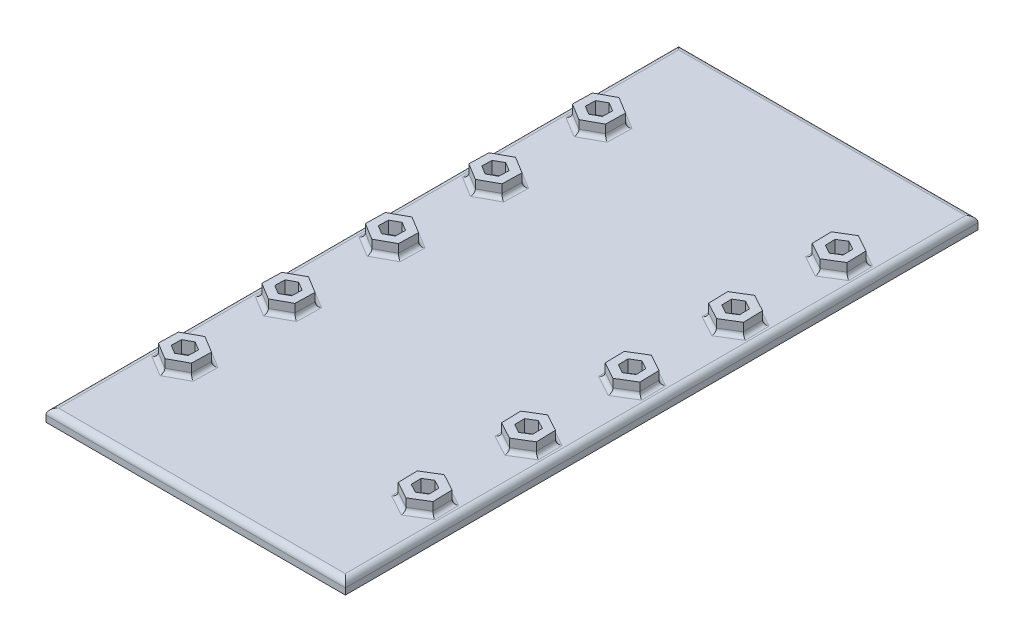
SolidWorks part; units mm, degrees
ref_plane "Front Plane" through (0, 0, 0) normal (0, 0, 1) x (1, 0, 0)
ref_plane "Top Plane" through (0, 0, 0) normal (0, 1, 0) x (1, 0, 0)
ref_plane "Right Plane" through (0, 0, 0) normal (1, 0, 0) x (0, 0, -1)
sketch "Sketch1" plane through (0, 0, 0) normal (0, 1, 0) x (1, 0, 0)
  line L0 (-26.85, 76.4) -> (-31.15, 76.4) construction
  line L1 (-36.15, 76.4) -> (36.15, 76.4)
  line L2 (-36.15, 76.4) -> (-36.15, -76.4)
  line L3 (-36.15, -76.4) -> (36.15, -76.4)
  line L4 (36.15, 76.4) -> (36.15, -76.4)
  line L5 (-36.15, 76.4) -> (36.15, -76.4) construction
  line L6 (-36.15, -76.4) -> (36.15, 76.4) construction
  line L8 (-31.15, 76.4) -> (-31.15, -76.4) construction
  point P0 (0, 0)
  dimension "D1" = 5
extrude "Boss-Extrude1" add sketch "Sketch1" along normal blind 3
sketch "Sketch2" plane through (0, 3, 0) normal (0, 1, 0) x (1, 0, 0)
  line L0 (-29, 76.4) -> (-29, -76.4) construction
  line L1 (-36.15, -76.4) -> (36.15, -76.4) construction
  line L2 (-29, 0) -> (-29, -25) construction
  circle A0 centre (-29, 0) radius 1.2
  circle A1 centre (-29, 0) radius 1.2 construction
  circle A2 centre (-29, -25) radius 1.2
  circle A3 centre (-29, -50) radius 1.2
  circle A4 centre (-29, 0) radius 1.2
  circle A5 centre (-29, -25) radius 1.2
  circle A6 centre (-29, 25) radius 1.2
  circle A7 centre (-29, 0) radius 1.2
  circle A8 centre (-29, 25) radius 1.2
  circle A9 centre (-29, 50) radius 1.2
  point P9 (-29, 0)
  dimension "D3" = 25
  dimension "D1" = 3
  dimension "D2" = 3
extrude "Cut-Extrude1" cut sketch "Sketch2" against normal up to next contours A3 | A2 | A0 | A6 | A9
mirror "Mirror1" about plane through (0, 0, 0) normal (1, 0, 0) of "Cut-Extrude1"
sketch "Sketch5" plane through (0, 3, 0) normal (0, 1, 0) x (1, 0, 0)
  line L0 (-29.1147, 20.2671) -> (-24.9586, 22.5342)
  line L1 (-27.0286, -1.2028) -> (-26.9726, 1.1059)
  line L2 (-26.9726, 1.1059) -> (-28.944, 2.3087)
  line L3 (-28.944, 2.3087) -> (-30.9714, 1.2028)
  line L4 (-30.9714, 1.2028) -> (-31.0274, -1.1059)
  line L5 (-31.0274, -1.1059) -> (-29.056, -2.3087)
  line L6 (-29.056, -2.3087) -> (-27.0286, -1.2028)
  line L7 (-29.0588, -2.4242) -> (-26.93, -1.263)
  line L8 (-26.93, -1.263) -> (-26.8712, 1.1612)
  line L9 (-26.8712, 1.1612) -> (-28.9412, 2.4242)
  line L10 (-28.9412, 2.4242) -> (-31.07, 1.263)
  line L11 (-31.07, 1.263) -> (-31.1288, -1.1612)
  line L12 (-31.1288, -1.1612) -> (-29.0588, -2.4242)
  line L13 (-29.1147, -4.7329) -> (-24.9586, -2.4658)
  line L14 (-24.9586, -2.4658) -> (-24.8438, 2.2671)
  line L15 (-24.8438, 2.2671) -> (-28.8853, 4.7329)
  line L16 (-28.8853, 4.7329) -> (-33.0414, 2.4658)
  line L17 (-33.0414, 2.4658) -> (-33.1562, -2.2671)
  line L18 (-33.1562, -2.2671) -> (-29.1147, -4.7329)
  line L19 (-29, 76.4) -> (-29, -76.4) construction
  line L20 (-36.15, -76.4) -> (36.15, -76.4) construction
  line L21 (-24.9586, 22.5342) -> (-24.8438, 27.2671)
  line L22 (-24.8438, 27.2671) -> (-28.8853, 29.7329)
  line L23 (-28.8853, 29.7329) -> (-33.0414, 27.4658)
  line L24 (-33.0414, 27.4658) -> (-33.1562, 22.7329)
  line L25 (-33.1562, 22.7329) -> (-29.1147, 20.2671)
  line L26 (-26.93, 23.737) -> (-26.8712, 26.1612)
  line L27 (-26.8712, 26.1612) -> (-28.9412, 27.4242)
  line L28 (-28.9412, 27.4242) -> (-31.07, 26.263)
  line L29 (-31.07, 26.263) -> (-31.1288, 23.8388)
  line L30 (-31.1288, 23.8388) -> (-29.0588, 22.5758)
  line L31 (-29.0588, 22.5758) -> (-26.93, 23.737)
  line L32 (-29.1147, 45.2671) -> (-24.9586, 47.5342)
  line L33 (-24.9586, 47.5342) -> (-24.8438, 52.2671)
  line L34 (-24.8438, 52.2671) -> (-28.8853, 54.7329)
  line L35 (-28.8853, 54.7329) -> (-33.0414, 52.4658)
  line L36 (-33.0414, 52.4658) -> (-33.1562, 47.7329)
  line L37 (-33.1562, 47.7329) -> (-29.1147, 45.2671)
  line L38 (-26.93, 48.737) -> (-26.8712, 51.1612)
  line L39 (-26.8712, 51.1612) -> (-28.9412, 52.4242)
  line L40 (-28.9412, 52.4242) -> (-31.07, 51.263)
  line L41 (-31.07, 51.263) -> (-31.1288, 48.8388)
  line L42 (-31.1288, 48.8388) -> (-29.0588, 47.5758)
  line L43 (-29.0588, 47.5758) -> (-26.93, 48.737)
  line L44 (-29.1147, -4.7329) -> (-24.9586, -2.4658)
  line L45 (-24.9586, -2.4658) -> (-24.8438, 2.2671)
  line L46 (-24.8438, 2.2671) -> (-28.8853, 4.7329)
  line L47 (-28.8853, 4.7329) -> (-33.0414, 2.4658)
  line L48 (-33.0414, 2.4658) -> (-33.1562, -2.2671)
  line L49 (-33.1562, -2.2671) -> (-29.1147, -4.7329)
  line L50 (-26.93, -1.263) -> (-26.8712, 1.1612)
  line L51 (-26.8712, 1.1612) -> (-28.9412, 2.4242)
  line L52 (-28.9412, 2.4242) -> (-31.07, 1.263)
  line L53 (-31.07, 1.263) -> (-31.1288, -1.1612)
  line L54 (-31.1288, -1.1612) -> (-29.0588, -2.4242)
  line L55 (-29.0588, -2.4242) -> (-26.93, -1.263)
  line L56 (-29.1147, 20.2671) -> (-24.9586, 22.5342)
  line L57 (-24.9586, 22.5342) -> (-24.8438, 27.2671)
  line L58 (-24.8438, 27.2671) -> (-28.8853, 29.7329)
  line L59 (-28.8853, 29.7329) -> (-33.0414, 27.4658)
  line L60 (-33.0414, 27.4658) -> (-33.1562, 22.7329)
  line L61 (-33.1562, 22.7329) -> (-29.1147, 20.2671)
  line L62 (-26.93, 23.737) -> (-26.8712, 26.1612)
  line L63 (-26.8712, 26.1612) -> (-28.9412, 27.4242)
  line L64 (-28.9412, 27.4242) -> (-31.07, 26.263)
  line L65 (-31.07, 26.263) -> (-31.1288, 23.8388)
  line L66 (-31.1288, 23.8388) -> (-29.0588, 22.5758)
  line L67 (-29.0588, 22.5758) -> (-26.93, 23.737)
  line L68 (-29.1147, -29.7329) -> (-24.9586, -27.4658)
  line L69 (-24.9586, -27.4658) -> (-24.8438, -22.7329)
  line L70 (-24.8438, -22.7329) -> (-28.8853, -20.2671)
  line L71 (-28.8853, -20.2671) -> (-33.0414, -22.5342)
  line L72 (-33.0414, -22.5342) -> (-33.1562, -27.2671)
  line L73 (-33.1562, -27.2671) -> (-29.1147, -29.7329)
  line L74 (-26.93, -26.263) -> (-26.8712, -23.8388)
  line L75 (-26.8712, -23.8388) -> (-28.9412, -22.5758)
  line L76 (-28.9412, -22.5758) -> (-31.07, -23.737)
  line L77 (-31.07, -23.737) -> (-31.1288, -26.1612)
  line L78 (-31.1288, -26.1612) -> (-29.0588, -27.4242)
  line L79 (-29.0588, -27.4242) -> (-26.93, -26.263)
  line L80 (-29.1147, -4.7329) -> (-24.9586, -2.4658)
  line L81 (-24.9586, -2.4658) -> (-24.8438, 2.2671)
  line L82 (-24.8438, 2.2671) -> (-28.8853, 4.7329)
  line L83 (-28.8853, 4.7329) -> (-33.0414, 2.4658)
  line L84 (-33.0414, 2.4658) -> (-33.1562, -2.2671)
  line L85 (-33.1562, -2.2671) -> (-29.1147, -4.7329)
  line L86 (-26.93, -1.263) -> (-26.8712, 1.1612)
  line L87 (-26.8712, 1.1612) -> (-28.9412, 2.4242)
  line L88 (-28.9412, 2.4242) -> (-31.07, 1.263)
  line L89 (-31.07, 1.263) -> (-31.1288, -1.1612)
  line L90 (-31.1288, -1.1612) -> (-29.0588, -2.4242)
  line L91 (-29.0588, -2.4242) -> (-26.93, -1.263)
  line L92 (-29.1147, -29.7329) -> (-24.9586, -27.4658)
  line L93 (-24.9586, -27.4658) -> (-24.8438, -22.7329)
  line L94 (-24.8438, -22.7329) -> (-28.8853, -20.2671)
  line L95 (-28.8853, -20.2671) -> (-33.0414, -22.5342)
  line L96 (-33.0414, -22.5342) -> (-33.1562, -27.2671)
  line L97 (-33.1562, -27.2671) -> (-29.1147, -29.7329)
  line L98 (-26.93, -26.263) -> (-26.8712, -23.8388)
  line L99 (-26.8712, -23.8388) -> (-28.9412, -22.5758)
  line L100 (-28.9412, -22.5758) -> (-31.07, -23.737)
  line L101 (-31.07, -23.737) -> (-31.1288, -26.1612)
  line L102 (-31.1288, -26.1612) -> (-29.0588, -27.4242)
  line L103 (-29.0588, -27.4242) -> (-26.93, -26.263)
  line L104 (-29.1147, -54.7329) -> (-24.9586, -52.4658)
  line L105 (-24.9586, -52.4658) -> (-24.8438, -47.7329)
  line L106 (-24.8438, -47.7329) -> (-28.8853, -45.2671)
  line L107 (-28.8853, -45.2671) -> (-33.0414, -47.5342)
  line L108 (-33.0414, -47.5342) -> (-33.1562, -52.2671)
  line L109 (-33.1562, -52.2671) -> (-29.1147, -54.7329)
  line L110 (-26.93, -51.263) -> (-26.8712, -48.8388)
  line L111 (-26.8712, -48.8388) -> (-28.9412, -47.5758)
  line L112 (-28.9412, -47.5758) -> (-31.07, -48.737)
  line L113 (-31.07, -48.737) -> (-31.1288, -51.1612)
  line L114 (-31.1288, -51.1612) -> (-29.0588, -52.4242)
  line L115 (-29.0588, -52.4242) -> (-26.93, -51.263)
  line L116 (-29.1147, -4.7329) -> (-29.1147, 20.2671) construction
  circle A0 centre (-29, 0) radius 2 construction
  arc A1 (-28, -1.7321) -> (-27, 0) centre (-29, 0) ccw construction
  point P30 (-29, 0)
  dimension "D5" = 25
  dimension "D1" = 0.1
  dimension "D2" = 2
  dimension "D3" = 3
  dimension "D4" = 3
extrude "Boss-Extrude2" add sketch "Sketch5" along normal blind 3 contours L108 L109 L104 L105 L106 L107 L115 L114 L113 L112 L111 L110 | L72 L73 L68 L69 L70 L71 L79 L78 L77 L76 L75 L74 | L17 L18 L13 L14 L15 L16 L12 L11 L10 L9 L8 L7 | L24 L25 L0 L21 L22 L23 L31 L30 L29 L28 L27 L26 | L36 L37 L32 L33 L34 L35 L43 L42 L41 L40 L39 L38
fillet "Fillet1" radius 1 30 edges at (-27.0366, 3, -46.4007) (-31.1354, 3, -46.5) (-33.0988, 3, -50.0994) (-30.9634, 3, -53.5993) (-26.8646, 3, -53.5) (-24.9012, 3, -49.9006) (-31.1354, 3, -21.5) (-27.0366, 3, -21.4007) (-24.9012, 3, -24.9006) (-26.8646, 3, -28.5) (-33.0988, 3, -25.0994) (-30.9634, 3, -28.5993) (-27.0366, 3, 3.5993) (-31.1354, 3, 3.5) (-33.0988, 3, -0.0994) (-30.9634, 3, -3.5993) (-26.8646, 3, -3.5) (-24.9012, 3, 0.0994) (-31.1354, 3, 28.5) (-33.0988, 3, 24.9006) (-30.9634, 3, 21.4007) (-26.8646, 3, 21.5) (-24.9012, 3, 25.0994) (-27.0366, 3, 28.5993) (-33.0988, 3, 49.9006) (-30.9634, 3, 46.4007) (-26.8646, 3, 46.5) (-24.9012, 3, 50.0994) (-31.1354, 3, 53.5) (-27.0366, 3, 53.5993)
mirror "Mirror2" about plane through (0, 0, 0) normal (1, 0, 0) of "Boss-Extrude2", "Fillet1"
fillet "Fillet2" radius 1.5 4 edges at (0, 3, -76.4) (-36.15, 3, 0) (36.15, 3, 0) (0, 3, 76.4)
